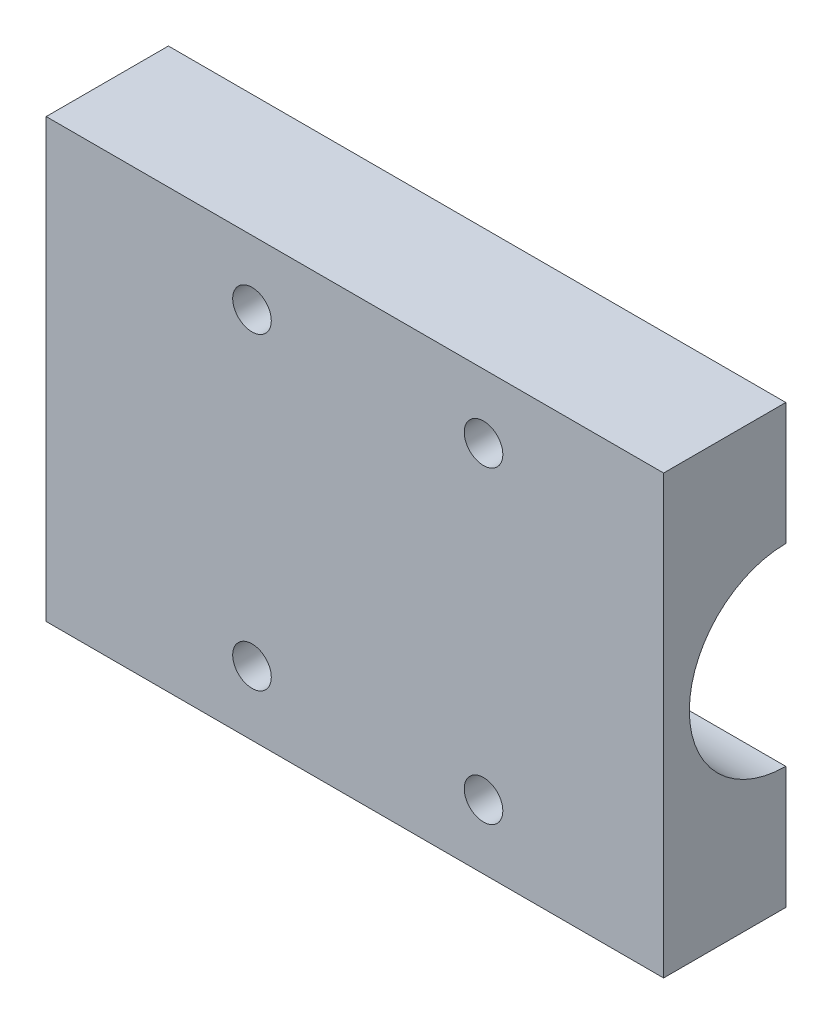
SolidWorks part; units mm, degrees
ref_plane "前视基准面" through (0, 0, 0) normal (0, 0, 1) x (1, 0, 0)
ref_plane "上视基准面" through (0, 0, 0) normal (0, 1, 0) x (1, 0, 0)
ref_plane "右视基准面" through (0, 0, 0) normal (1, 0, 0) x (0, 0, -1)
sketch "草图1" plane through (0, 0, 0) normal (0, 0, 1) x (1, 0, 0)
  line L0 (-12.3352, -2.5866) -> (3.6648, -2.5866) construction
  line L1 (-12.3352, 14.4134) -> (35.6648, 14.4134)
  line L2 (-12.3352, 14.4134) -> (-12.3352, -19.5866)
  line L3 (-12.3352, -19.5866) -> (35.6648, -19.5866)
  line L4 (35.6648, 14.4134) -> (35.6648, -19.5866)
  line L5 (3.6648, 9.4134) -> (3.6648, -14.5866)
  line L6 (3.6648, -2.5866) -> (21.6648, -2.5866) construction
  line L7 (21.6648, 9.4134) -> (21.6648, -14.5866)
  circle A0 centre (3.6648, 9.4134) radius 1.5
  circle A1 centre (3.6648, -14.5866) radius 1.5
  circle A2 centre (21.6648, 9.4134) radius 1.5
  circle A3 centre (21.6648, -14.5866) radius 1.5
  point P8 (3.6648, -2.5866)
  point P15 (21.6648, -2.5866)
  dimension "D5" = 18
  dimension "D1" = 48
  dimension "D2" = 34
  dimension "D3" = 16
  dimension "D4" = 24
extrude "凸台-拉伸1" add sketch "草图1" along normal blind 9.5
sketch "草图2" plane through (-12.3352, 0, 0) normal (-1, 0, 0) x (0, 0, 1)
  line L0 (0, 14.4134) -> (0, -19.5866) construction
  circle A0 centre (0, -2.5866) radius 7.5
extrude "切除-拉伸1" cut sketch "草图2" against normal blind 49.5
